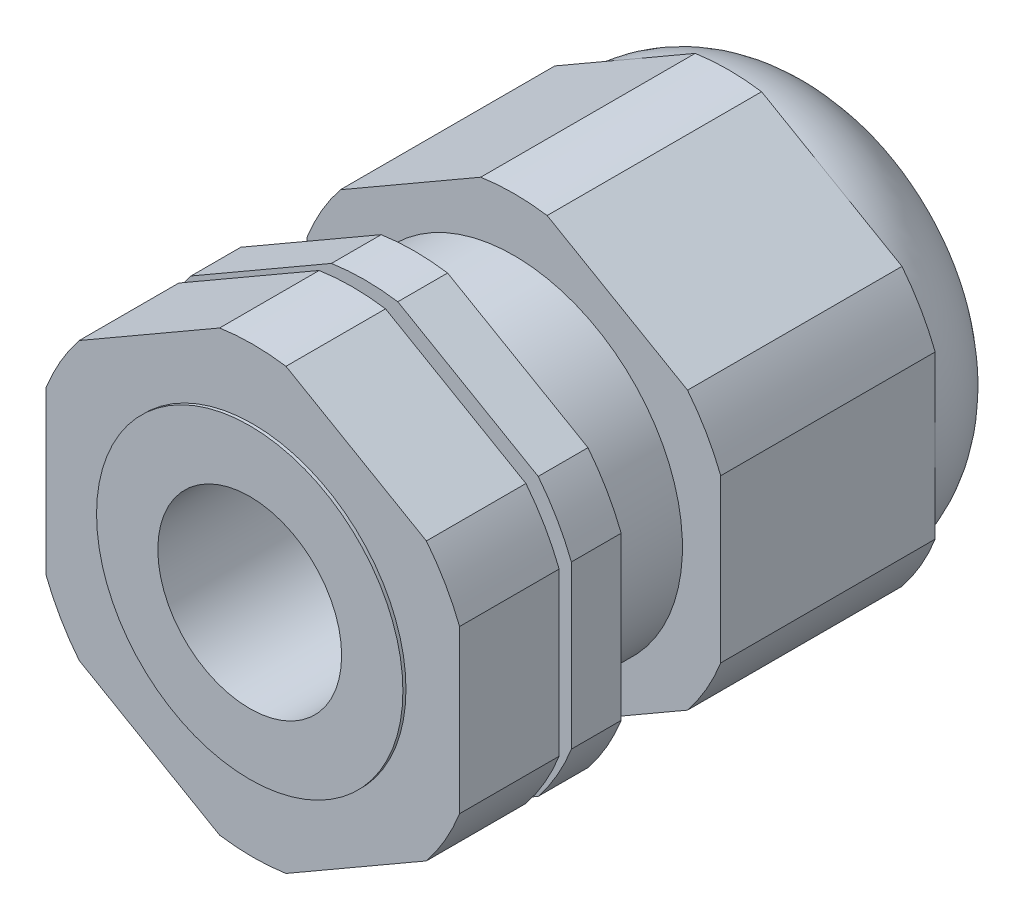
SolidWorks part; units mm, degrees
material "ABS"
ref_plane "Front Plane" through (0, 0, 0) normal (0, 0, 1) x (1, 0, 0)
ref_plane "Top Plane" through (0, 0, 0) normal (0, 1, 0) x (1, 0, 0)
ref_plane "Right Plane" through (0, 0, 0) normal (1, 0, 0) x (0, 0, -1)
sketch "Sketch1" plane through (0, 0, 0) normal (1, 0, 0) x (0, 0, -1)
  line L0 (-7.5, 0) -> (30.5, 0) construction
  line L1 (-7.5, 10) -> (-7.3, 10)
  line L2 (0, 10) -> (0, 14.5)
  line L7 (0, 14.5) -> (30.5, 14.5)
  line L8 (30.5, 14.5) -> (30.5, 6)
  line L9 (30.5, 6) -> (-7.5, 6)
  line L10 (-7.5, 6) -> (-7.5, 10)
  line L12 (-7.3, 10) -> (-7.3, 14.5)
  line L13 (-7.3, 14.5) -> (-0.8, 14.5)
  line L14 (-0.8, 14.5) -> (-0.8, 10)
  line L15 (-0.8, 10) -> (0, 10)
  dimension "D3" = 20
  dimension "D6" = 29
  dimension "D7" = 0.8
revolve "Revolve1" add sketch "Sketch1" angle 360 about L0
sketch "Sketch2" plane through (0, 0, 7.3) normal (0, 0, 1) x (1, 0, 0)
  line L1 (0, 15.5885) -> (-13.5, 7.7942)
  line L2 (-13.5, 7.7942) -> (-13.5, -7.7942)
  line L3 (-13.5, -7.7942) -> (0, -15.5885)
  line L4 (0, -15.5885) -> (13.5, -7.7942)
  line L5 (13.5, -7.7942) -> (13.5, 7.7942)
  line L6 (13.5, 7.7942) -> (0, 15.5885)
  circle A0 centre (0, 0) radius 13.5 construction
extrude "Cut-Extrude1" cut sketch "Sketch2" against normal through all flip side to cut
sketch "Sketch3" plane through (0, 0, 0) normal (0, 1, 0) x (1, 0, 0)
  line L0 (-13.5, 0) -> (-13.5, 30.5) construction
  line L1 (-2.1674, 30.5) -> (-11.3326, 30.5) construction
  line L2 (0, 30.5) -> (0, 0) construction
  line L3 (2.1674, 30.5) -> (-2.1674, 30.5) construction
  line L4 (-6.75, 30.5) -> (-6.75, 35.5)
  line L5 (-6.75, 35.5) -> (-61.4469, 35.5)
  line L6 (-61.4469, 35.5) -> (-61.4469, 23.75)
  line L7 (-61.4469, 23.75) -> (-13.5, 23.75)
  line L8 (-13.5, 0) -> (-13.5, 30.5) construction
  line L9 (-16, 9.75) -> (-11, 9.75)
  line L10 (-16, 9.75) -> (-16, 3.25)
  line L11 (-16, 3.25) -> (-11, 3.25)
  line L12 (-11, 9.75) -> (-11, 3.25)
  line L13 (-16, 9.75) -> (-11, 3.25) construction
  line L14 (-16, 3.25) -> (-11, 9.75) construction
  line L15 (-10, 0) -> (-10, -0.8) construction
  line L16 (-13.5, -7.3) -> (-13.5, -0.8) construction
  line L17 (-13.5, 3.25) -> (-13.5, 0) construction
  line L18 (-13.5, -4.05) -> (-13.5, -7.3) construction
  arc A0 (-13.5, 23.75) -> (-6.75, 30.5) centre (-6.75, 23.75) cw
  point P9 (-13.5, 6.5)
  dimension "D1" = 5
  dimension "D2" = 1
revolve "Cut-Revolve3" cut sketch "Sketch3" angle 360 about L2
equation "\"B\"= 27"
equation "\"D\"= 20"
equation "\"D1\"= 12"
equation "\"D2\"= 29"
equation "\"L\"= 38"
equation "\"L1\"= 7.5"
equation "\"L2\"= 6.5"
equation "\"D1@Sketch2\"= \"B\""
equation "\"D3@Sketch1\"= \"D\""
equation "\"D4@Sketch1\"= \"D1\""
equation "\"D6@Sketch1\"= \"D2\""
equation "\"D1@Sketch1\"= \"L\""
equation "\"D2@Sketch1\"= \"L1\""
equation "\"D8@Sketch1\"= \"L2\""
